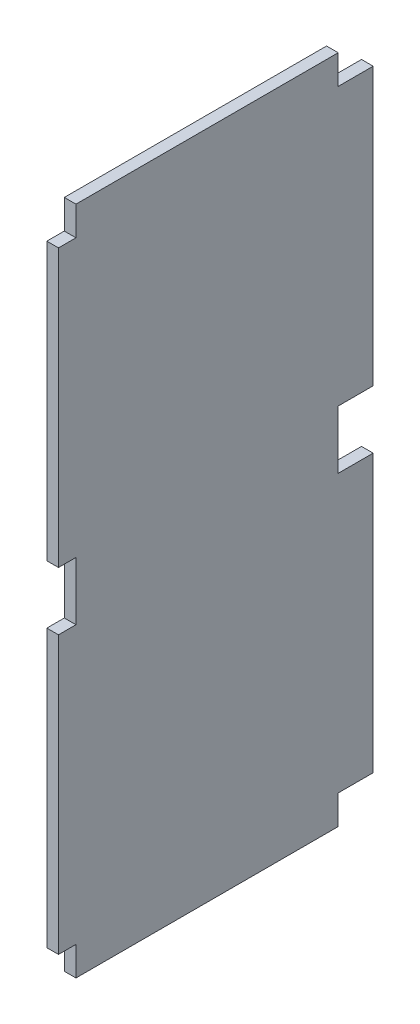
SolidWorks part; units mm, degrees
material "PVC rigido"
ref_plane "Piano frontale" through (0, 0, 0) normal (0, 0, 1) x (1, 0, 0)
ref_plane "Piano superiore" through (0, 0, 0) normal (0, 1, 0) x (1, 0, 0)
ref_plane "Piano destro" through (0, 0, 0) normal (1, 0, 0) x (0, 0, -1)
sketch "Schizzo1" plane through (0, 0, 0) normal (0, 0, 1) x (1, 0, 0)
  line L1 (6, 52.5) -> (4, 52.5)
  line L2 (6, 52.5) -> (6, -52.5)
  line L3 (6, -52.5) -> (4, -52.5)
  line L4 (4, 52.5) -> (4, -52.5)
extrude "Estrusione-Estrusione1" add sketch "Schizzo1" along normal up to surface (48 mm away) and the other way up to surface (6 mm away)
ref_plane "Piano1" through (0, 0, 0) normal (0, -1, 0) x (-1, 0, 0)
sketch "Schizzo2" plane through (6, 0, 0) normal (1, 0, 0) x (0, 0, -1)
  line L0 (-48, -52.5) -> (-48, 52.5) construction
  line L1 (-48, -5) -> (-45, -5)
  line L2 (-48, -5) -> (-48, 5)
  line L3 (-48, 5) -> (-45, 5)
  line L4 (-45, 5) -> (-45, 0)
  line L5 (6, -52.5) -> (6, 52.5) construction
  line L6 (6, -5) -> (0, -5)
  line L7 (6, -5) -> (6, 5)
  line L8 (6, 5) -> (0, 5)
  line L9 (0, 5) -> (0, 0)
  line L11 (-45, 0) -> (-45, -5)
  line L12 (-1.65, 0) -> (1.65, 0) construction
  line L13 (0, 0) -> (0, -5)
  line L14 (-45, -5) -> (-48, -5) construction
extrude "Taglio-Estrusione1" cut sketch "Schizzo2" against normal blind 10
sketch "Schizzo3" plane through (0, -52.5, 0) normal (0, -1, 0) x (1, 0, 0)
  line L0 (6, 48) -> (6, -6) construction
  line L1 (4, 0) -> (6, 0)
  line L2 (4, 0) -> (4, 45)
  line L3 (4, 45) -> (6, 45)
  line L4 (6, 0) -> (6, 45)
extrude "Estrusione-Estrusione2" add sketch "Schizzo3" along normal blind 5
mirror "Specchia1" about plane through (0, 0, 0) normal (0, -1, 0) of "Estrusione-Estrusione2"
